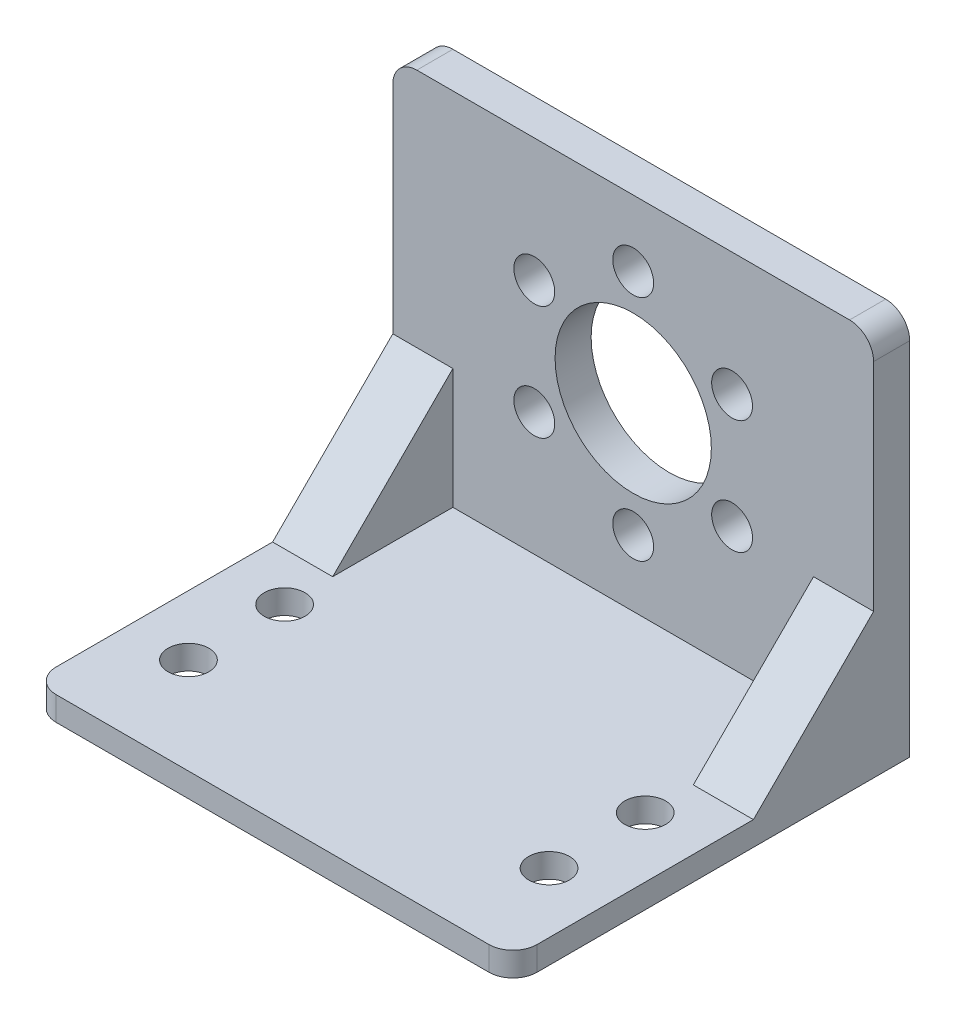
SolidWorks part; units mm, degrees
material "6061 合金"
ref_plane "前视基准面" through (0, 0, 0) normal (0, 0, 1) x (1, 0, 0)
ref_plane "上视基准面" through (0, 0, 0) normal (0, 1, 0) x (1, 0, 0)
ref_plane "右视基准面" through (0, 0, 0) normal (1, 0, 0) x (0, 0, -1)
sketch "草图1" plane through (0, 0, 0) normal (0, 1, 0) x (1, 0, 0)
  line L1 (-20, -20) -> (20, -20)
  line L2 (-20, -20) -> (-20, 20)
  line L3 (-20, 20) -> (20, 20)
  line L4 (20, -20) -> (20, 20)
  line L5 (-20, -20) -> (20, 20) construction
  line L6 (-20, 20) -> (20, -20) construction
  point P0 (0, 0)
  dimension "D1" = 40
  dimension "D2" = 40
sketch "草图2" plane through (0, 0, 0) normal (0, 0, 1) x (1, 0, 0)
  line L1 (20, 0) -> (-20, 0)
  line L2 (20, 0) -> (20, 32)
  line L3 (20, 32) -> (-20, 32)
  line L4 (-20, 0) -> (-20, 32)
  circle A0 centre (0, 17) radius 9.5 construction
  circle A1 centre (0, 26.5) radius 1.7
  circle A2 centre (8.2272, 21.75) radius 1.7
  circle A3 centre (8.2272, 12.25) radius 1.7
  circle A4 centre (0, 7.5) radius 1.7
  circle A5 centre (-8.2272, 12.25) radius 1.7
  circle A6 centre (-8.2272, 21.75) radius 1.7
  point P4 (0, 32)
  point P23 (0, 17)
  dimension "D3" = 15
  dimension "D4" = 19
  dimension "D5" = 3.4
  dimension "D1" = 40
  dimension "D2" = 32
  dimension "D6" = 6
extrude "凸台-拉伸2" add sketch "草图2" along normal blind 3
sketch "草图3" plane through (0, 0, 3) normal (0, 0, 1) x (1, 0, 0)
  line L1 (20, 32) -> (-20, 32) construction
  circle A0 centre (0, 17) radius 6.5
  dimension "D1" = 15
  dimension "D2" = 13
extrude "切除-拉伸1" cut sketch "草图3" against normal up to next
sketch "草图4" plane through (0, 0, 3) normal (0, 0, 1) x (1, 0, 0)
  line L0 (-20, 32) -> (-20, 0) construction
  line L1 (-20, 2) -> (20, 2)
  line L2 (-20, 2) -> (-20, 0)
  line L3 (-20, 0) -> (20, 0)
  line L4 (20, 2) -> (20, 0)
  dimension "D1" = 2
extrude "凸台-拉伸3" add sketch "草图4" along normal blind 30
sketch "草图5" plane through (-20, 0, 0) normal (-1, 0, 0) x (0, 0, 1)
  line L0 (3, 12) -> (13, 2)
  line L1 (3, 32) -> (3, 2) construction
  line L2 (13, 2) -> (3, 2)
  line L3 (3, 2) -> (3, 12)
  dimension "D1" = 10
extrude "凸台-拉伸4" add sketch "草图5" against normal blind 5
mirror "镜向1" about plane through (0, 0, 0) normal (1, 0, 0) of "凸台-拉伸4"
fillet "圆角1" radius 2 4 edges at (20, 1, 33) (-20, 1, 33) (-20, 32, 1.5) (20, 32, 1.5)
sketch "草图6" plane through (0, 2, 0) normal (0, 1, 0) x (1, 0, 0)
  line L0 (0, 0) -> (0, -10.1087) construction
  line L1 (-20, -31) -> (-20, -13) construction
  line L2 (18, -33) -> (-18, -33) construction
  circle A0 centre (-15, -17) radius 1.7
  circle A1 centre (15, -17) radius 1.7
  circle A2 centre (-15, -25) radius 1.7
  circle A3 centre (15, -25) radius 1.7
  dimension "D1" = 3.4
  dimension "D2" = 8
  dimension "D4" = 8
  dimension "D3" = 5
extrude "切除-拉伸2" cut sketch "草图6" against normal blind 10
